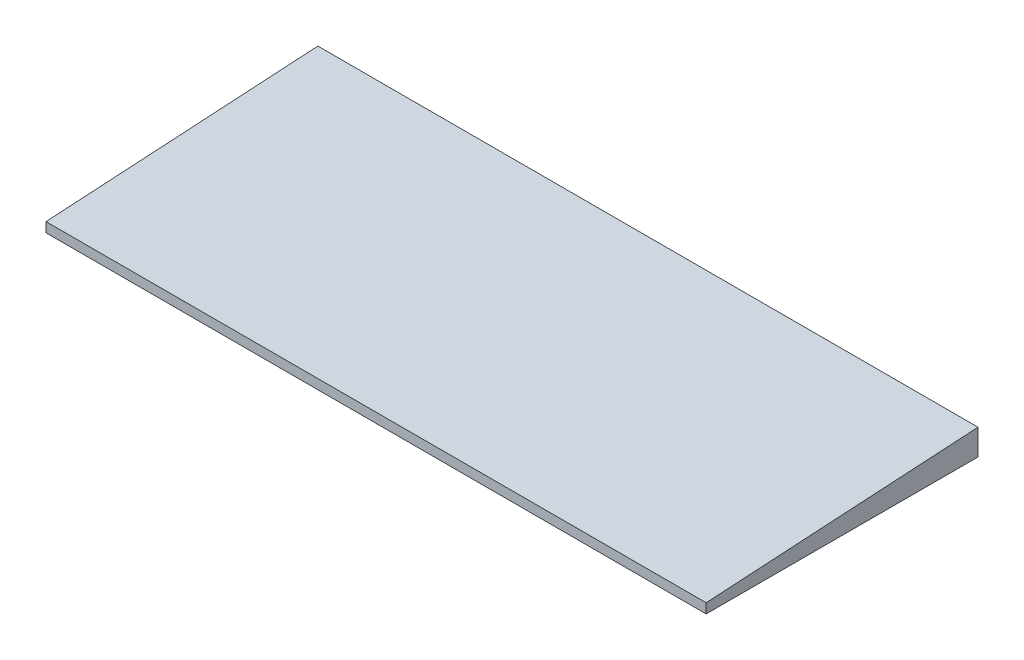
SolidWorks part; units mm, degrees
ref_plane "Ebene vorne" through (0, 0, 0) normal (0, 0, 1) x (1, 0, 0)
ref_plane "Ebene oben" through (0, 0, 0) normal (0, 1, 0) x (1, 0, 0)
ref_plane "Ebene rechts" through (0, 0, 0) normal (1, 0, 0) x (0, 0, -1)
sketch "Skizze1" plane through (0, 0, 0) normal (1, 0, 0) x (0, 0, -1)
  line L0 (0, 0) -> (114.9, 0)
  line L1 (114.9, 0) -> (114.9, 10.9)
  line L2 (114.9, 10.9) -> (0, 4.1)
  line L3 (0, 4.1) -> (0, 0)
  dimension "D1" = 4.1
  dimension "D2" = 10.9
  dimension "D3" = 114.9
extrude "Aufsatz-Linear austragen1" add sketch "Skizze1" along normal blind 279
